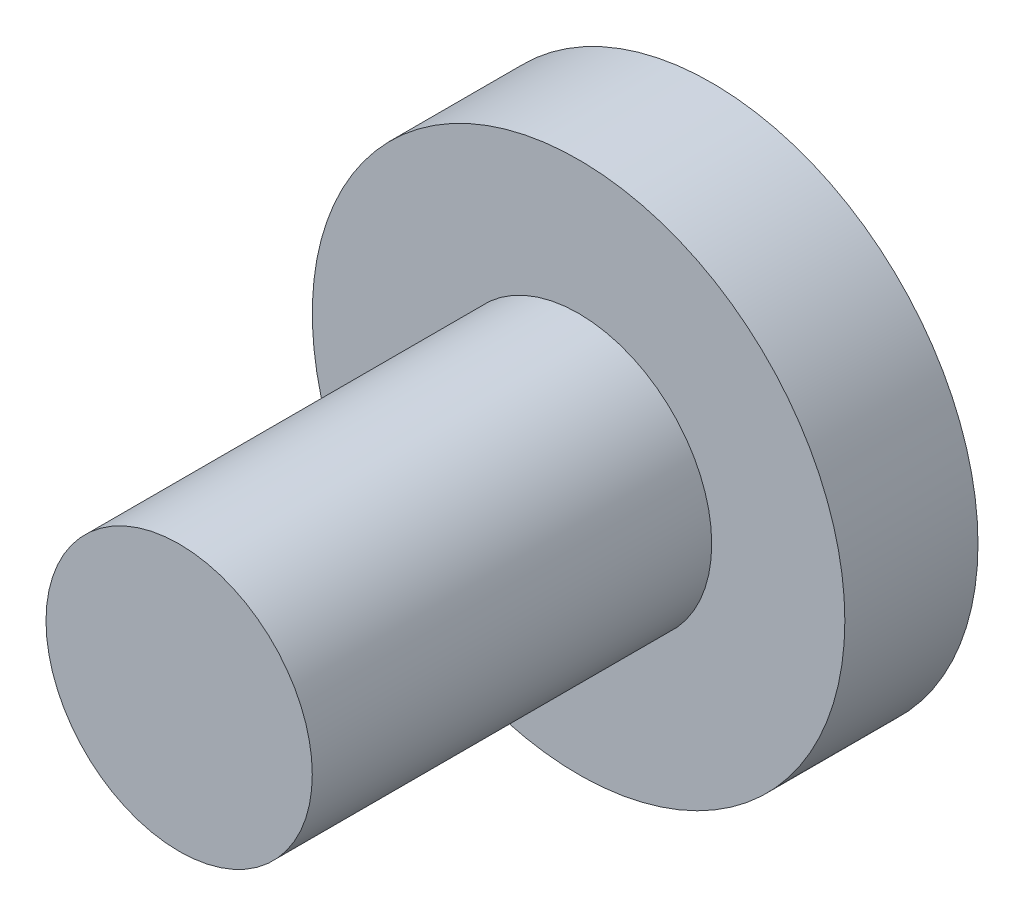
SolidWorks part; units mm, degrees
ref_plane "前视基准面" through (0, 0, 0) normal (0, 0, 1) x (1, 0, 0)
ref_plane "上视基准面" through (0, 0, 0) normal (0, 1, 0) x (1, 0, 0)
ref_plane "右视基准面" through (0, 0, 0) normal (1, 0, 0) x (0, 0, -1)
sketch "草图1" plane through (0, 0, 0) normal (0, 0, 1) x (1, 0, 0)
  circle A0 centre (0, 0) radius 10
extrude "凸台-拉伸1" add sketch "草图1" along normal blind 5
sketch "草图2" plane through (0, 0, 5) normal (0, 0, 1) x (1, 0, 0)
  circle A0 centre (0, 0) radius 5
extrude "凸台-拉伸2" add sketch "草图2" along normal blind 15
